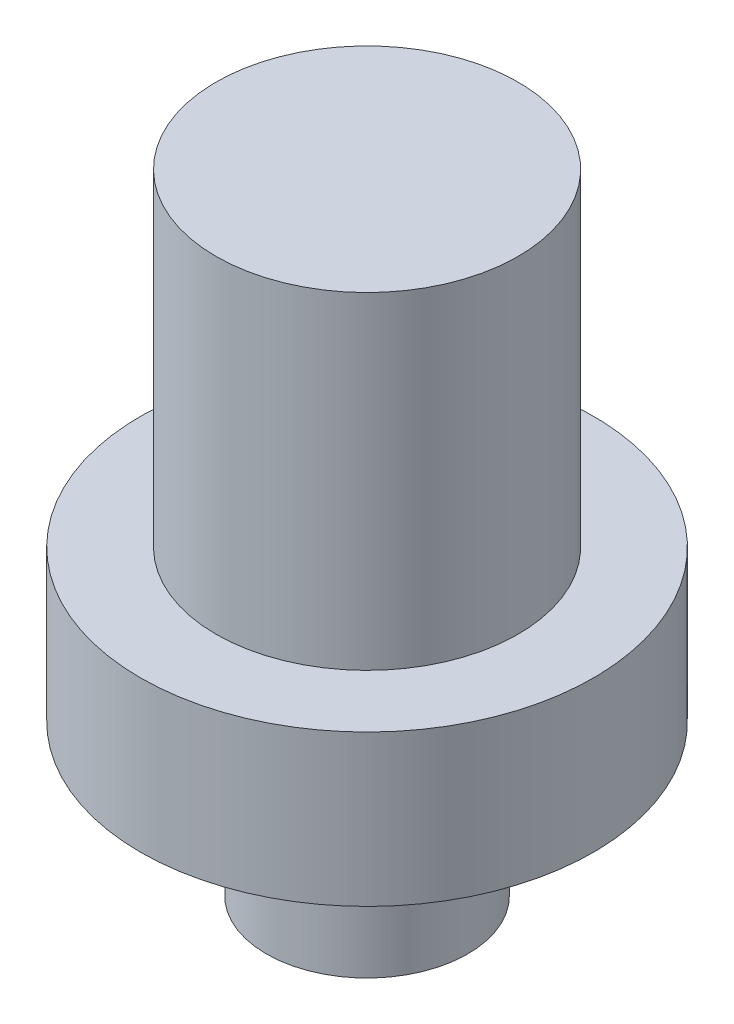
SolidWorks part; units mm, degrees
ref_plane "Спереди" through (0, 0, 0) normal (0, 0, 1) x (1, 0, 0)
ref_plane "Сверху" through (0, 0, 0) normal (0, 1, 0) x (1, 0, 0)
ref_plane "Справа" through (0, 0, 0) normal (1, 0, 0) x (0, 0, -1)
other "Configuration Table"
sketch "Sketch1" plane through (0, 0, 0) normal (0, 0, 1) x (1, 0, 0)
  line L0 (0, 4.5715) -> (0, -4.14) construction
  line L1 (0, -3) -> (2, -3)
  line L2 (2, -3) -> (2, 0)
  line L3 (2, 0) -> (4.5, 0)
  line L4 (4.5, 0) -> (4.5, 3)
  line L5 (4.5, 3) -> (3, 3)
  line L6 (3, 3) -> (3, 9.5)
  line L7 (3, 9.5) -> (0, 9.5)
  line L13 (0, 9.5) -> (0, -3)
  dimension "D1" = 3
  dimension "D2" = 4
  dimension "D3" = 9
  dimension "D4" = 6
  dimension "D5" = 3
  dimension "D6" = 6.5
revolve "Revolve1" add sketch "Sketch1" angle 360 about L0
